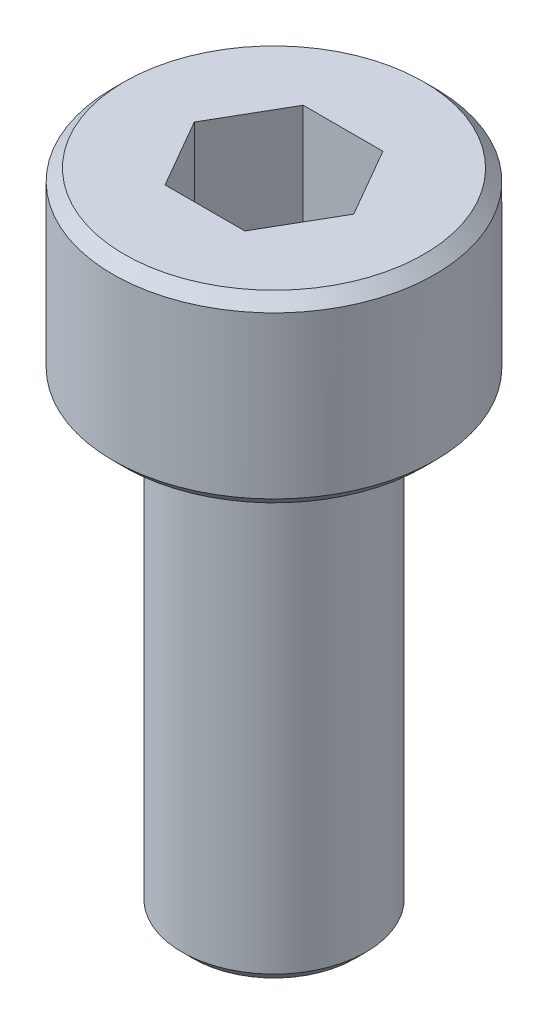
SolidWorks part; units mm, degrees
ref_plane "Front Plane" through (0, 0, 0) normal (0, 0, 1) x (1, 0, 0)
ref_plane "Top Plane" through (0, 0, 0) normal (0, 1, 0) x (1, 0, 0)
ref_plane "Right Plane" through (0, 0, 0) normal (1, 0, 0) x (0, 0, -1)
sketch "Sketch1" plane through (0, 0, 0) normal (0, 0, 1) x (1, 0, 0)
  line L0 (0, 4) -> (-3.5, 4)
  line L1 (-3.5, 4) -> (-3.5, 0)
  line L2 (-3.5, 0) -> (-2, 0)
  line L3 (-2, 0) -> (-2, -10)
  line L4 (-2, -10) -> (0, -10)
  line L5 (0, -10) -> (0, 0)
  line L6 (0, 0) -> (0, 4)
  line L7 (0, -10) -> (0, -12.6046) construction
  dimension "D1" = 10
  dimension "D2" = 4
  dimension "D3" = 7
  dimension "D4" = 4
revolve "Revolve1" add sketch "Sketch1" angle 360 about L7
sketch "Sketch2" plane through (0, 4, 0) normal (0, 1, 0) x (1, 0, 0)
  line L1 (0.866, 1.5) -> (-0.866, 1.5)
  line L2 (-0.866, 1.5) -> (-1.7321, 0)
  line L3 (-1.7321, 0) -> (-0.866, -1.5)
  line L4 (-0.866, -1.5) -> (0.866, -1.5)
  line L5 (0.866, -1.5) -> (1.7321, 0)
  line L6 (1.7321, 0) -> (0.866, 1.5)
  circle A0 centre (0, 0) radius 1.5 construction
  dimension "D1" = 3
extrude "Cut-Extrude1" cut sketch "Sketch2" against normal blind 3
chamfer "Chamfer1" distance 0.25 angle 45 3 edges at (-3.5, 0, 0) (-3.5, 4, 0) (-2, -10, 0)
